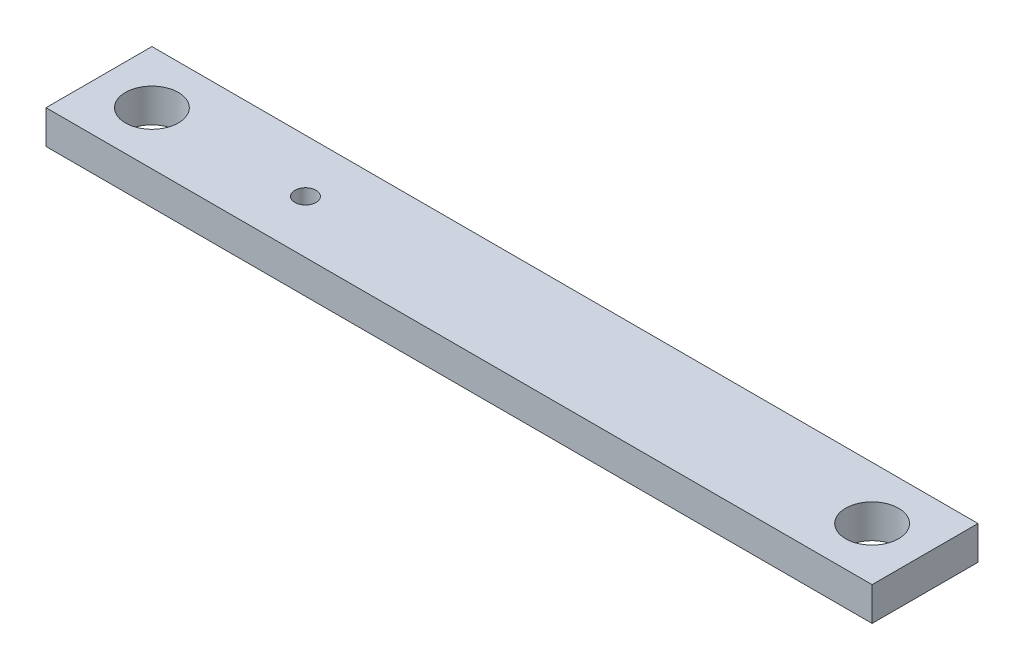
SolidWorks part; units mm, degrees
ref_plane "Front Plane" through (0, 0, 0) normal (0, 0, 1) x (1, 0, 0)
ref_plane "Top Plane" through (0, 0, 0) normal (0, 1, 0) x (1, 0, 0)
ref_plane "Right Plane" through (0, 0, 0) normal (1, 0, 0) x (0, 0, -1)
sketch "Sketch2" plane through (0, 0, 0) normal (0, 1, 0) x (1, 0, 0)
  line L1 (-39, -5) -> (39, -5)
  line L2 (-39, -5) -> (-39, 5)
  line L3 (-39, 5) -> (39, 5)
  line L4 (39, -5) -> (39, 5)
  line L5 (-39, -5) -> (39, 5) construction
  line L6 (-39, 5) -> (39, -5) construction
  point P0 (0, 0)
  dimension "D1" = 78
  dimension "D2" = 10
extrude "Boss-Extrude1" add sketch "Sketch2" along normal blind 3.175
sketch "Sketch3" plane through (0, 3.175, 0) normal (0, 1, 0) x (1, 0, 0)
  line L0 (-64.0944, 0) -> (61.2196, 0) construction
  line L1 (0, 21.5935) -> (0, -26.8203) construction
  circle A0 centre (-34, 0) radius 2.5
  circle A1 centre (34, 0) radius 2.5
  dimension "D1" = 5
  dimension "D2" = 34
extrude "Cut-Extrude1" cut sketch "Sketch3" against normal up to surface (3.175 mm away) up to face at (0, 0, 0)
sketch "Sketch4" plane through (0, 3.175, 0) normal (0, 1, 0) x (1, 0, 0)
  line L0 (-39, 0) -> (0, 0) construction
  line L3 (-39, 5) -> (-39, -5) construction
  circle A0 centre (-19.5, 0) radius 1
  point P4 (0, 0)
  dimension "D1" = 2
extrude "Cut-Extrude2" cut sketch "Sketch4" against normal up to next
